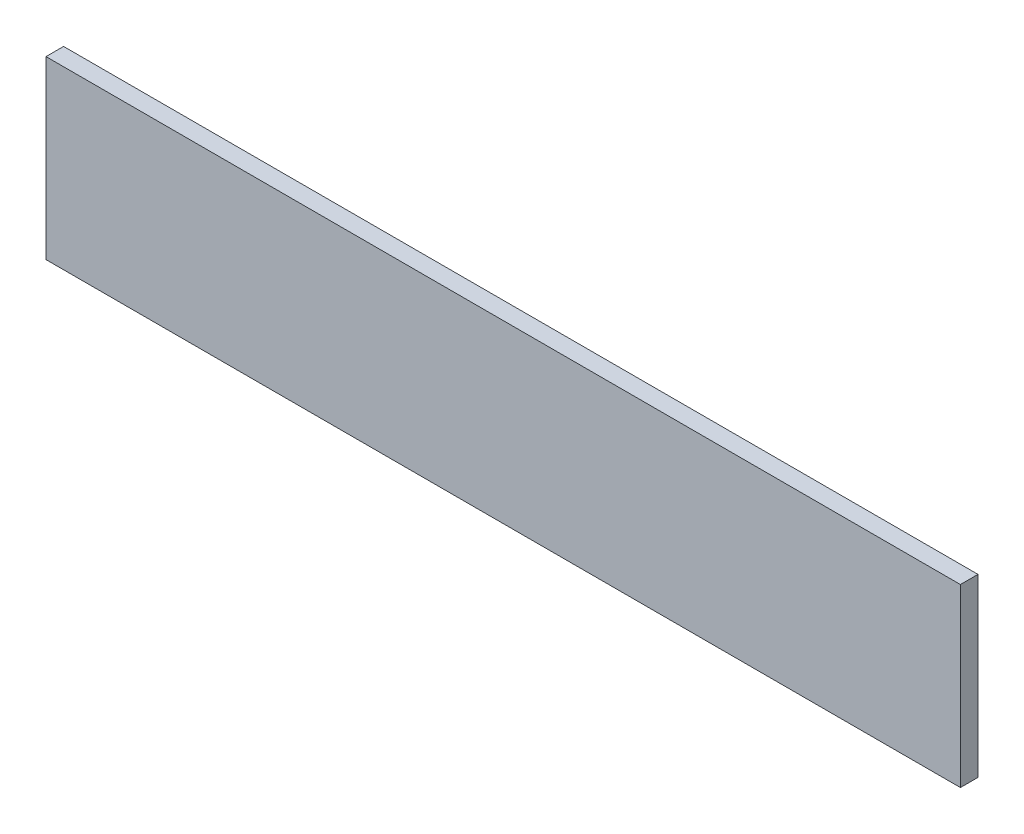
SolidWorks part; units mm, degrees
ref_plane "Plan de face" through (0, 0, 0) normal (0, 0, 1) x (1, 0, 0)
ref_plane "Plan de dessus" through (0, 0, 0) normal (0, 1, 0) x (1, 0, 0)
ref_plane "Plan de droite" through (0, 0, 0) normal (1, 0, 0) x (0, 0, -1)
sketch "Esquisse1" plane through (0, 0, 0) normal (0, 0, 1) x (1, 0, 0)
  line L1 (0, 0) -> (260, 0)
  line L2 (0, 0) -> (0, -50)
  line L3 (0, -50) -> (260, -50)
  line L4 (260, 0) -> (260, -50)
  dimension "D1" = 260
  dimension "D2" = 50
extrude "Boss.-Extru.1" add sketch "Esquisse1" along normal blind 5
